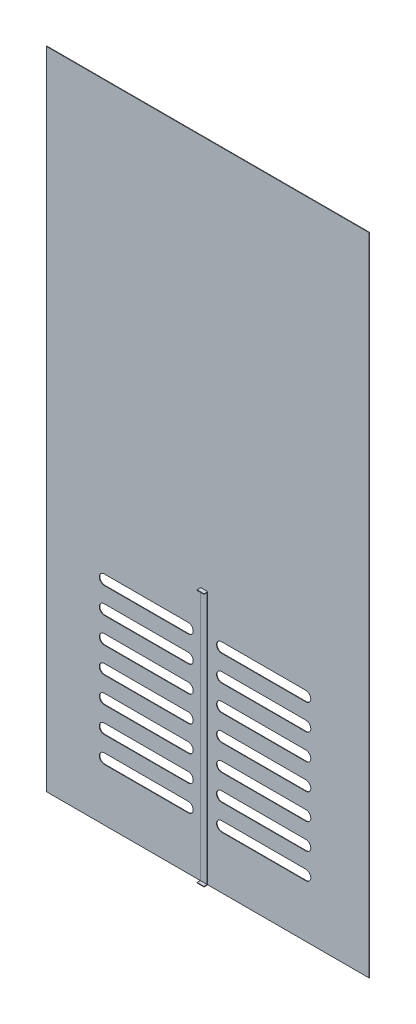
SolidWorks part; units mm, degrees
ref_plane "Front Plane" through (0, 0, 0) normal (0, 0, 1) x (1, 0, 0)
ref_plane "Top Plane" through (0, 0, 0) normal (0, 1, 0) x (1, 0, 0)
ref_plane "Right Plane" through (0, 0, 0) normal (1, 0, 0) x (0, 0, -1)
sketch "Sketch1" plane through (0, 0, 0) normal (0, 0, 1) x (1, 0, 0)
  line L1 (0, 0) -> (500, 0)
  line L2 (0, 0) -> (0, 1000)
  line L3 (0, 1000) -> (500, 1000)
  line L4 (500, 0) -> (500, 1000)
  line L6 (263.6642, 329.1843) -> (271.4054, 329.1843)
  line L7 (409.6315, 329.1843) -> (401.8903, 329.1843)
  line L8 (89.7592, 329.1843) -> (219.7747, 329.1843) construction
  line L9 (89.7592, 336.9255) -> (219.7747, 336.9255)
  line L23 (89.7592, 321.4431) -> (219.7747, 321.4431)
  line L24 (271.4054, 329.1843) -> (401.8903, 329.1843) construction
  line L25 (271.4054, 336.9255) -> (401.8903, 336.9255)
  line L26 (271.4054, 321.4431) -> (401.8903, 321.4431)
  line L27 (89.7592, 329.1843) -> (82.018, 329.1843)
  line L28 (227.5159, 329.1843) -> (219.7747, 329.1843)
  line L29 (401.8903, 329.1843) -> (409.6315, 329.1843)
  line L30 (271.4054, 329.1843) -> (263.6642, 329.1843)
  line L31 (271.4054, 289.1843) -> (401.8903, 289.1843) construction
  line L32 (271.4054, 281.4431) -> (401.8903, 281.4431)
  line L33 (271.4054, 296.9255) -> (401.8903, 296.9255)
  line L34 (89.7592, 289.1843) -> (219.7747, 289.1843) construction
  line L35 (89.7592, 281.4431) -> (219.7747, 281.4431)
  line L36 (89.7592, 296.9255) -> (219.7747, 296.9255)
  line L37 (271.4054, 249.1843) -> (401.8903, 249.1843) construction
  line L38 (271.4054, 256.9255) -> (401.8903, 256.9255)
  line L39 (271.4054, 241.4431) -> (401.8903, 241.4431)
  line L40 (271.4054, 209.1843) -> (401.8903, 209.1843) construction
  line L41 (271.4054, 201.4431) -> (401.8903, 201.4431)
  line L42 (271.4054, 216.9255) -> (401.8903, 216.9255)
  line L43 (89.7592, 249.1843) -> (219.7747, 249.1843) construction
  line L44 (89.7592, 256.9255) -> (219.7747, 256.9255)
  line L45 (89.7592, 241.4431) -> (219.7747, 241.4431)
  line L46 (89.7592, 209.1843) -> (219.7747, 209.1843) construction
  line L47 (89.7592, 201.4431) -> (219.7747, 201.4431)
  line L48 (89.7592, 216.9255) -> (219.7747, 216.9255)
  line L49 (271.4054, 169.1843) -> (401.8903, 169.1843) construction
  line L50 (271.4054, 176.9255) -> (401.8903, 176.9255)
  line L51 (271.4054, 161.4431) -> (401.8903, 161.4431)
  line L52 (89.7592, 169.1843) -> (219.7747, 169.1843) construction
  line L53 (89.7592, 176.9255) -> (219.7747, 176.9255)
  line L54 (89.7592, 161.4431) -> (219.7747, 161.4431)
  line L55 (89.7592, 129.1843) -> (219.7747, 129.1843) construction
  line L56 (89.7592, 121.4431) -> (219.7747, 121.4431)
  line L57 (89.7592, 136.9255) -> (219.7747, 136.9255)
  line L58 (271.4054, 129.1843) -> (401.8903, 129.1843) construction
  line L59 (271.4054, 121.4431) -> (401.8903, 121.4431)
  line L60 (271.4054, 136.9255) -> (401.8903, 136.9255)
  line L61 (271.4054, 89.1843) -> (401.8903, 89.1843) construction
  line L62 (271.4054, 96.9255) -> (401.8903, 96.9255)
  line L63 (271.4054, 81.4431) -> (401.8903, 81.4431)
  line L64 (89.7592, 89.1843) -> (219.7747, 89.1843) construction
  line L65 (89.7592, 96.9255) -> (219.7747, 96.9255)
  line L66 (89.7592, 81.4431) -> (219.7747, 81.4431)
  arc A0 (89.7592, 336.9255) -> (89.7592, 321.4431) centre (89.7592, 329.1843) ccw
  arc A1 (219.7747, 321.4431) -> (219.7747, 336.9255) centre (219.7747, 329.1843) ccw
  arc A2 (271.4054, 336.9255) -> (271.4054, 321.4431) centre (271.4054, 329.1843) ccw
  arc A3 (401.8903, 321.4431) -> (401.8903, 336.9255) centre (401.8903, 329.1843) ccw
  arc A4 (271.4054, 281.4431) -> (271.4054, 296.9255) centre (271.4054, 289.1843) cw
  arc A5 (401.8903, 296.9255) -> (401.8903, 281.4431) centre (401.8903, 289.1843) cw
  arc A6 (89.7592, 281.4431) -> (89.7592, 296.9255) centre (89.7592, 289.1843) cw
  arc A7 (219.7747, 296.9255) -> (219.7747, 281.4431) centre (219.7747, 289.1843) cw
  arc A8 (271.4054, 256.9255) -> (271.4054, 241.4431) centre (271.4054, 249.1843) ccw
  arc A9 (401.8903, 241.4431) -> (401.8903, 256.9255) centre (401.8903, 249.1843) ccw
  arc A10 (271.4054, 201.4431) -> (271.4054, 216.9255) centre (271.4054, 209.1843) cw
  arc A11 (401.8903, 216.9255) -> (401.8903, 201.4431) centre (401.8903, 209.1843) cw
  arc A12 (89.7592, 256.9255) -> (89.7592, 241.4431) centre (89.7592, 249.1843) ccw
  arc A13 (219.7747, 241.4431) -> (219.7747, 256.9255) centre (219.7747, 249.1843) ccw
  arc A14 (89.7592, 201.4431) -> (89.7592, 216.9255) centre (89.7592, 209.1843) cw
  arc A15 (219.7747, 216.9255) -> (219.7747, 201.4431) centre (219.7747, 209.1843) cw
  arc A16 (271.4054, 176.9255) -> (271.4054, 161.4431) centre (271.4054, 169.1843) ccw
  arc A17 (401.8903, 161.4431) -> (401.8903, 176.9255) centre (401.8903, 169.1843) ccw
  arc A18 (89.7592, 176.9255) -> (89.7592, 161.4431) centre (89.7592, 169.1843) ccw
  arc A19 (219.7747, 161.4431) -> (219.7747, 176.9255) centre (219.7747, 169.1843) ccw
  arc A20 (89.7592, 121.4431) -> (89.7592, 136.9255) centre (89.7592, 129.1843) cw
  arc A21 (219.7747, 136.9255) -> (219.7747, 121.4431) centre (219.7747, 129.1843) cw
  arc A22 (271.4054, 121.4431) -> (271.4054, 136.9255) centre (271.4054, 129.1843) cw
  arc A23 (401.8903, 136.9255) -> (401.8903, 121.4431) centre (401.8903, 129.1843) cw
  arc A24 (271.4054, 96.9255) -> (271.4054, 81.4431) centre (271.4054, 89.1843) ccw
  arc A25 (401.8903, 81.4431) -> (401.8903, 96.9255) centre (401.8903, 89.1843) ccw
  arc A26 (89.7592, 96.9255) -> (89.7592, 81.4431) centre (89.7592, 89.1843) ccw
  arc A27 (219.7747, 81.4431) -> (219.7747, 96.9255) centre (219.7747, 89.1843) ccw
  point P13 (154.767, 329.1843)
  point P18 (336.6479, 329.1843)
  point P47 (336.6479, 289.1843)
  point P54 (154.767, 289.1843)
  point P61 (336.6479, 249.1843)
  point P68 (336.6479, 209.1843)
  point P75 (154.767, 249.1843)
  point P82 (154.767, 209.1843)
  point P89 (336.6479, 169.1843)
  point P96 (154.767, 169.1843)
  point P103 (154.767, 129.1843)
  point P110 (336.6479, 129.1843)
  point P117 (336.6479, 89.1843)
  point P124 (154.767, 89.1843)
extrude "Boss-Extrude1" add sketch "Sketch1" along normal blind 0.8 contours L1 L4 L3 L2 A27 L66 A26 L65 A25 L63 A24 L62 A19 L54 A18 L53 A17 L51 A16 L50 A13 L45 A12 L44 A9 L39 A8 L38 A3 L26 A2 L25 A1 L23 A0 L9 L33 A5
sketch "Sketch4" plane through (0, 0, 0.8) normal (0, 0, 1) x (1, 0, 0)
  line L0 (0, 0) -> (500, 0) construction
  line L1 (239.2172, 0) -> (250, 0)
  line L2 (239.2172, 0) -> (239.2172, 393.4)
  line L3 (239.2172, 393.4) -> (250, 393.4)
  line L4 (250, 0) -> (250, 393.4)
extrude "Boss-Extrude3" add sketch "Sketch4" along normal blind 0.8
sketch "Sketch6" plane through (0, 393.4, 0) normal (0, 1, 0) x (1, 0, 0)
  line L0 (239.2172, -1.6) -> (239.2172, -6.6)
  line L1 (239.2172, -6.6) -> (250, -6.6)
  line L2 (250, -1.6) -> (250, -6.6)
  line L7 (250, -0.8) -> (239.2172, -0.8)
  line L8 (239.2172, -0.8) -> (239.2172, -1.6)
  line L9 (239.2172, -1.6) -> (250, -1.6)
  line L10 (250, -1.6) -> (250, -0.8)
  line L13 (239.2172, -1.6) -> (250, -1.6)
  dimension "D1" = 0
extrude "Boss-Extrude4" add sketch "Sketch6" against normal blind 0.8
ref_plane "Plane1" through (0, 0, 0) normal (0, -1, 0) x (-1, 0, 0)
sketch "Sketch7" plane through (0, 0, 0) normal (0, -1, 0) x (-1, 0, 0)
  line L0 (-250, -1.6) -> (-250, -6.6)
  line L1 (-250, -6.6) -> (-239.2172, -6.6)
  line L2 (-239.2172, -1.6) -> (-239.2172, -6.6)
  line L3 (-239.2172, -1.6) -> (-239.2172, -0.8) construction
  line L4 (-239.2172, -1.6) -> (-250, -1.6) construction
  line L5 (-239.2172, -1.6) -> (-250, -1.6)
extrude "Boss-Extrude5" add sketch "Sketch7" against normal blind 0.8
ref_plane "Plane2" through (500, 1000, 0) normal (0, 1, 0) x (1, 0, 0)
